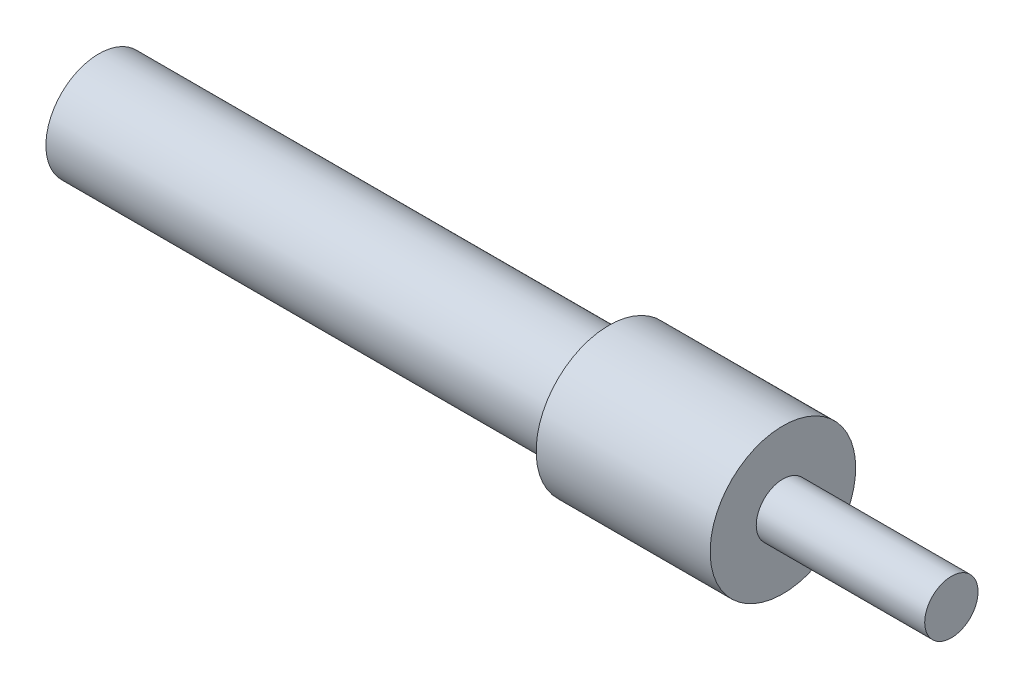
SolidWorks part; units mm, degrees
ref_plane "Front Plane" through (0, 0, 0) normal (1, 0, 0) x (0, 1, 0)
ref_plane "Top Plane" through (0, 0, 0) normal (0, 0, 1) x (0, 1, 0)
ref_plane "Right Plane" through (0, 0, 0) normal (0, 1, 0) x (-1, 0, 0)
sketch "Sketch1" plane through (0, 0, 0) normal (1, 0, 0) x (0, 1, 0)
  circle A0 centre (0, 0) radius 6.48
  dimension "D1" = 12.96
extrude "Boss-Extrude1" add sketch "Sketch1" along normal blind 15.494
sketch "Sketch2" plane through (15.494, 0, 0) normal (1, 0, 0) x (0, 1, 0)
  circle A0 centre (0, 0) radius 4.715
  dimension "D1" = 9.43
extrude "Boss-Extrude2" add sketch "Sketch2" against normal blind 60.91
sketch "Sketch3" plane through (15.494, 0, 0) normal (-1, 0, 0) x (0, -1, 0)
  circle A0 centre (0, 0) radius 2.375
  dimension "D1" = 4.75
extrude "Boss-Extrude3" add sketch "Sketch3" against normal blind 15
